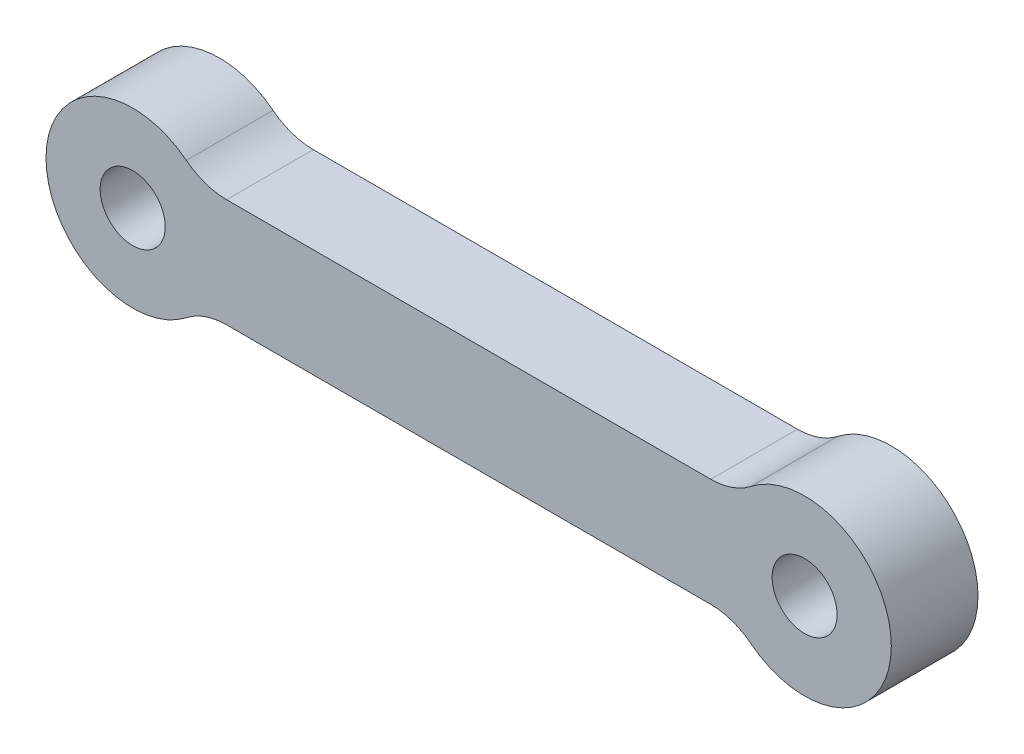
SolidWorks part; units mm, degrees
ref_plane "Front Plane" through (0, 0, 0) normal (0, 0, 1) x (1, 0, 0)
ref_plane "Top Plane" through (0, 0, 0) normal (0, 1, 0) x (1, 0, 0)
ref_plane "Right Plane" through (0, 0, 0) normal (1, 0, 0) x (0, 0, -1)
sketch "Sketch1" plane through (0, 0, 0) normal (0, 0, 1) x (1, 0, 0)
  line L0 (15.5, 0) -> (-15.5, 0) construction
  line L1 (0, 7.8634) -> (0, -6.3512) construction
  line L3 (11.1699, -2.5) -> (-11.1699, -2.5)
  line L5 (11.1699, 2.5) -> (-11.1699, 2.5)
  line L7 (12.3775, -2.5) -> (-12.3775, 2.5) construction
  line L8 (12.3775, 2.5) -> (-12.3775, -2.5) construction
  arc A0 (-13.0256, 3.1429) -> (-13.0256, -3.1429) centre (-15.5, 0) ccw
  circle A1 centre (-15.5, 0) radius 1.5
  circle A2 centre (15.5, 0) radius 1.5
  arc A3 (13.0256, 3.1429) -> (13.0256, -3.1429) centre (15.5, 0) cw
  arc A4 (11.1699, -2.5) -> (13.0256, -3.1429) centre (11.1699, -5.5) cw
  arc A5 (13.0256, 3.1429) -> (11.1699, 2.5) centre (11.1699, 5.5) cw
  arc A6 (-11.1699, -2.5) -> (-13.0256, -3.1429) centre (-11.1699, -5.5) ccw
  arc A7 (-11.1699, 2.5) -> (-13.0256, 3.1429) centre (-11.1699, 5.5) cw
  point P3 (0, 0)
  point P4 (0, 0)
  dimension "D2" = 8
  dimension "D3" = 3
  dimension "D5" = 3
  dimension "D1" = 31
  dimension "D4" = 5
extrude "Boss-Extrude1" add sketch "Sketch1" along normal blind 4
